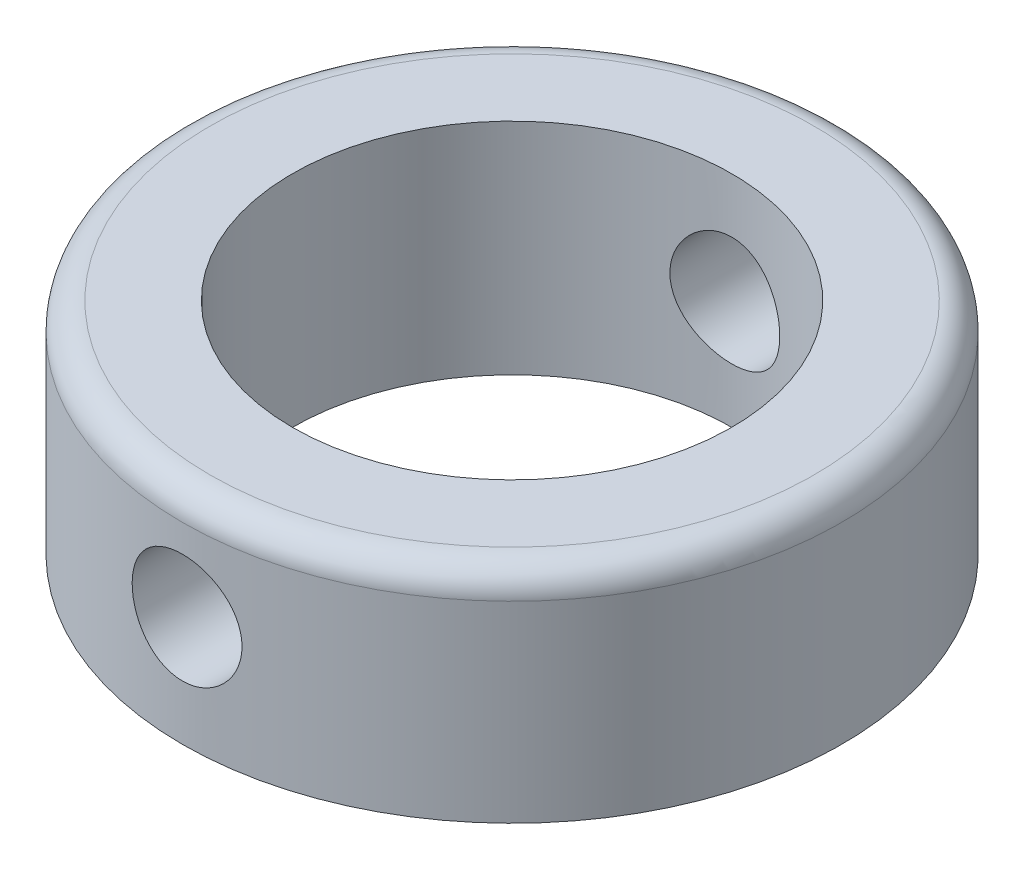
SolidWorks part; units mm, degrees
ref_plane "Front Plane" through (0, 0, 0) normal (0, 0, 1) x (1, 0, 0)
ref_plane "Top Plane" through (0, 0, 0) normal (0, 1, 0) x (1, 0, 0)
ref_plane "Right Plane" through (0, 0, 0) normal (1, 0, 0) x (0, 0, -1)
sketch "Sketch1" plane through (0, 0, 0) normal (0, 1, 0) x (1, 0, 0)
  circle A0 centre (0, 0) radius 8
  circle A1 centre (0, 0) radius 12
  dimension "D1" = 24
  dimension "D2" = 16
extrude "Boss-Extrude1" add sketch "Sketch1" along normal blind 8
fillet "Fillet1" radius 1 1 edges at (0, 8, 12)
sketch "Sketch2" plane through (0, 0, 0) normal (0, 0, 1) x (1, 0, 0)
  line L0 (-12, 0) -> (12, 0) construction
  circle A0 centre (0, 4) radius 2
  dimension "D1" = 4
  dimension "D2" = 4
extrude "Cut-Extrude1" cut sketch "Sketch2" against normal through all both and the other way through all
